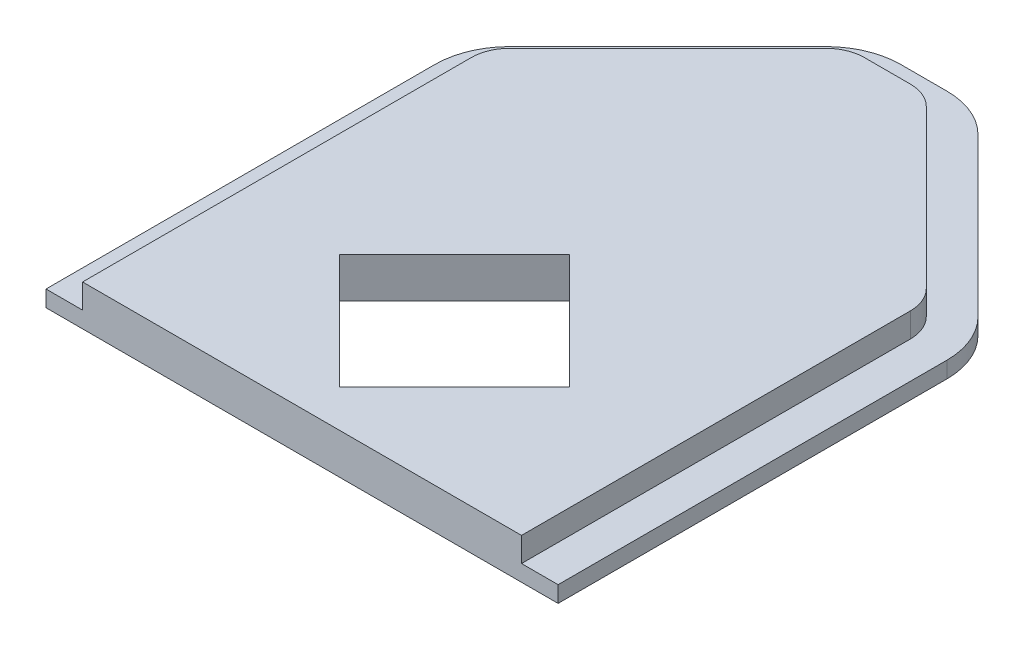
SolidWorks part; units mm, degrees
ref_plane "Front Plane" through (0, 0, 0) normal (0, 0, 1) x (1, 0, 0)
ref_plane "Top Plane" through (0, 0, 0) normal (0, 1, 0) x (1, 0, 0)
ref_plane "Right Plane" through (0, 0, 0) normal (1, 0, 0) x (0, 0, -1)
sketch "Sketch1" plane through (0, 0, 0) normal (0, 1, 0) x (1, 0, 0)
  line L0 (0, 0) -> (0, 20) construction
  line L1 (11, 0) -> (-11, 0) construction
  line L2 (-11, 0) -> (-11, 20) construction
  line L3 (11, 0) -> (11, 20) construction
  line L4 (-11, 20) -> (-2, 29) construction
  line L5 (11, 20) -> (2, 29) construction
  line L6 (-2, 29) -> (2, 29) construction
  line L7 (-10.8, 0) -> (-10.8, 19.9172)
  line L8 (-10.8, 19.9172) -> (-1.9172, 28.8)
  line L9 (-1.9172, 28.8) -> (1.9172, 28.8)
  line L10 (10.8, 19.9172) -> (1.9172, 28.8)
  line L11 (10.8, 0) -> (10.8, 19.9172)
  line L12 (-10.8, 0) -> (10.8, 0)
  dimension "D1" = 22
  dimension "D2" = 4
  dimension "D3" = 135
  dimension "D4" = 20
  dimension "D5" = 0.2
extrude "Boss-Extrude1" add sketch "Sketch1" along normal blind 2
fillet "Fillet1" radius 1.9 4 edges at (10.8, 1, -19.9172) (1.9172, 1, -28.8) (-1.9172, 1, -28.8) (-10.8, 1, -19.9172)
sketch "Sketch2" plane through (0, 0, 0) normal (0, -1, 0) x (1, 0, 0)
  line L32 (12.6, 0) -> (-12.6, 0)
  line L37 (-12.6, -19.1302) -> (-12.6, 0)
  line L38 (-3.7464, -29.5163) -> (-11.5163, -21.7464)
  line L39 (1.1302, -30.6) -> (-1.1302, -30.6)
  line L40 (11.5163, -21.7464) -> (3.7464, -29.5163)
  line L41 (12.6, 0) -> (12.6, -19.1302)
  line L42 (-12.6, -19.1302) -> (-12.6, 0)
  line L43 (-3.7464, -29.5163) -> (-11.5163, -21.7464)
  line L44 (1.1302, -30.6) -> (-1.1302, -30.6)
  line L45 (11.5163, -21.7464) -> (3.7464, -29.5163)
  line L46 (12.6, 0) -> (12.6, -19.1302)
  arc A8 (-12.6, -19.1302) -> (-11.5163, -21.7464) centre (-8.9, -19.1302) ccw
  arc A9 (-3.7464, -29.5163) -> (-1.1302, -30.6) centre (-1.1302, -26.9) ccw
  arc A10 (1.1302, -30.6) -> (3.7464, -29.5163) centre (1.1302, -26.9) ccw
  arc A11 (11.5163, -21.7464) -> (12.6, -19.1302) centre (8.9, -19.1302) ccw
  arc A12 (-12.6, -19.1302) -> (-11.5163, -21.7464) centre (-8.9, -19.1302) ccw
  arc A13 (-3.7464, -29.5163) -> (-1.1302, -30.6) centre (-1.1302, -26.9) ccw
  arc A14 (1.1302, -30.6) -> (3.7464, -29.5163) centre (1.1302, -26.9) ccw
  arc A15 (11.5163, -21.7464) -> (12.6, -19.1302) centre (8.9, -19.1302) ccw
  dimension "D1" = 1.8
extrude "Boss-Extrude2" add sketch "Sketch2" against normal blind 0.8
sketch "Sketch3" plane through (0, 2, 0) normal (0, 1, 0) x (1, 0, 0)
  line L0 (0, 0) -> (0, 15) construction
  line L1 (5.6569, 7.5) -> (0, 13.1569)
  line L2 (5.6569, 7.5) -> (0, 1.8431)
  line L3 (0, 13.1569) -> (-5.6569, 7.5)
  line L4 (0, 1.8431) -> (-5.6569, 7.5)
  line L5 (5.6569, 7.5) -> (-5.6569, 7.5) construction
  line L6 (0, 13.1569) -> (0, 1.8431) construction
  point P4 (0, 7.5)
  dimension "D2" = 8
  dimension "D1" = 15
extrude "Cut-Extrude1" cut sketch "Sketch3" against normal up to next
